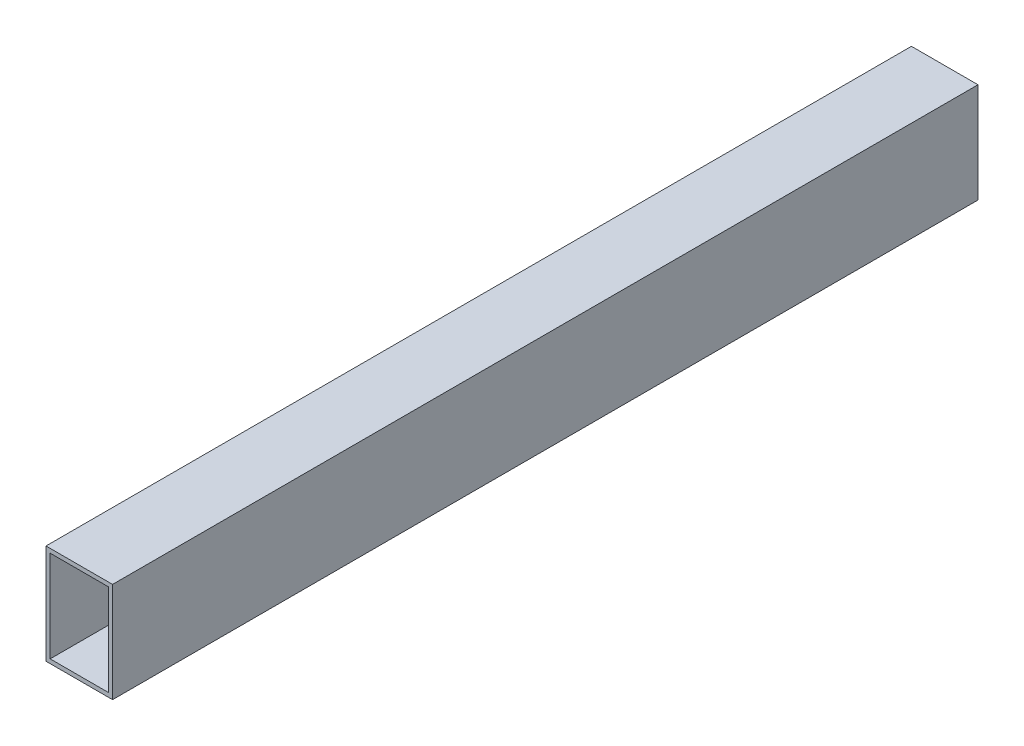
SolidWorks part; units mm, degrees
ref_plane "Front Plane" through (0, 0, 0) normal (0, 0, 1) x (1, 0, 0)
ref_plane "Top Plane" through (0, 0, 0) normal (0, 1, 0) x (1, 0, 0)
ref_plane "Right Plane" through (0, 0, 0) normal (1, 0, 0) x (0, 0, -1)
sketch "Sketch1" plane through (0, 0, 0) normal (0, 0, 1) x (1, 0, 0)
  line L1 (-25.4, 38.1) -> (25.4, 38.1)
  line L2 (-25.4, 38.1) -> (-25.4, -38.1)
  line L3 (-25.4, -38.1) -> (25.4, -38.1)
  line L4 (25.4, 38.1) -> (25.4, -38.1)
  line L5 (-25.4, 38.1) -> (25.4, -38.1) construction
  line L6 (-25.4, -38.1) -> (25.4, 38.1) construction
  point P0 (0, 0)
  dimension "D1" = 50.8
  dimension "D2" = 76.2
extrude "Boss-Extrude1" add sketch "Sketch1" along normal blind 660.4
shell "Shell1" thickness 3.175
